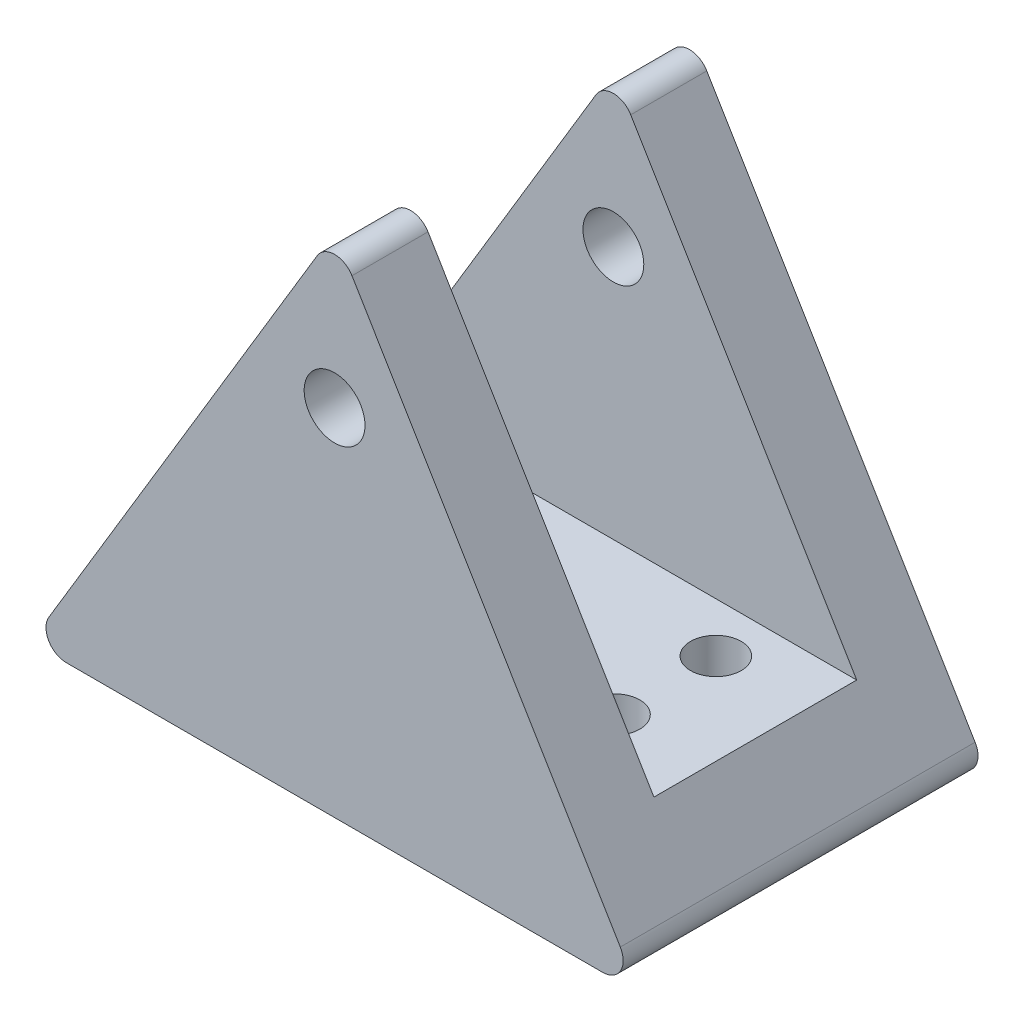
SolidWorks part; units mm, degrees
material "6061-T6 (SS)"
ref_plane "Front Plane" through (0, 0, 0) normal (0, 0, 1) x (1, 0, 0)
ref_plane "Top Plane" through (0, 0, 0) normal (0, 1, 0) x (1, 0, 0)
ref_plane "Right Plane" through (0, 0, 0) normal (1, 0, 0) x (0, 0, -1)
sketch "Sketch2" plane through (0, 0, 0) normal (0, 0, 1) x (1, 0, 0)
  line L1 (-38.1, 31.75) -> (38.1, 31.75)
  line L2 (-38.1, 31.75) -> (-38.1, -31.75)
  line L3 (-38.1, -31.75) -> (38.1, -31.75)
  line L4 (38.1, 31.75) -> (38.1, -31.75)
  line L5 (-38.1, 31.75) -> (38.1, -31.75) construction
  line L6 (-38.1, -31.75) -> (38.1, 31.75) construction
  point P0 (0, 0)
  dimension "D1" = 76.2
  dimension "D2" = 63.5
extrude "Boss-Extrude1" add sketch "Sketch2" along normal blind 44.45
sketch "Sketch3" plane through (0, 0, 44.45) normal (0, 0, 1) x (1, 0, 0)
  line L0 (0, 31.75) -> (0, -31.75) construction
  line L1 (-38.1, -31.75) -> (38.1, -31.75) construction
  line L2 (-38.1, -31.75) -> (0, 31.75)
  line L4 (-38.1, 31.75) -> (-38.1, -31.75)
  line L7 (-38.1, 31.75) -> (0, 31.75)
  point P6 (0, 0)
sketch "Sketch5" plane through (38.1, 0, 0) normal (1, 0, 0) x (0, 0, -1)
  line L0 (0, 0) -> (-44.45, 0) construction
  line L1 (-44.45, 0) -> (-22.225, 31.75) construction
  line L2 (-44.45, 31.75) -> (0, 31.75) construction
  line L3 (-22.225, 31.75) -> (-22.225, -31.75) construction
  line L4 (-44.45, -31.75) -> (0, -31.75) construction
  line L5 (-34.925, -19.05) -> (-9.525, -19.05)
  line L6 (-34.925, -19.05) -> (-34.925, 31.75)
  line L7 (-34.925, 31.75) -> (-9.525, 31.75)
  line L8 (-9.525, 31.75) -> (-9.525, -19.05)
  point P13 (-22.225, -19.05)
  dimension "D1" = 25.4
  dimension "D2" = 50.8
extrude "Cut-Extrude3" cut sketch "Sketch5" against normal through all
extrude "Cut-Extrude4" cut sketch "Sketch3" against normal blind 44.45
sketch "Sketch6" plane through (0, 0, 44.45) normal (0, 0, 1) x (1, 0, 0)
  line L0 (0, 31.75) -> (38.1, -31.75)
  line L1 (38.1, -31.75) -> (38.1, 31.75)
  line L2 (38.1, 31.75) -> (0, 31.75)
extrude "Cut-Extrude5" cut sketch "Sketch6" against normal through all
sketch "Sketch7" plane through (0, -19.05, 0) normal (0, 1, 0) x (1, 0, 0)
  line L0 (0, 0) -> (0, -44.1741) construction
  line L1 (-30.48, -22.087) -> (30.48, -22.087) construction
  line L2 (30.48, -34.925) -> (30.48, -9.525) construction
  line L4 (-38.1, -44.45) -> (-38.1, 0) construction
  circle A0 centre (-19.05, -15.737) radius 3.175
  circle A1 centre (19.05, -15.737) radius 3.175
  circle A2 centre (19.05, -28.437) radius 3.175
  circle A3 centre (-19.05, -28.437) radius 3.175
  point P9 (0, -22.087)
  dimension "D1" = 6.35
  dimension "D2" = 6.35
  dimension "D3" = 19.05
extrude "Cut-Extrude6" cut sketch "Sketch7" against normal blind 44.45
sketch "Sketch8" plane through (0, 0, 44.45) normal (0, 0, 1) x (1, 0, 0)
  line L0 (0, 31.75) -> (0, 8.89) construction
  circle A0 centre (0, 12.7) radius 3.81
  point P6 (0, 0)
  dimension "D1" = 7.62
  dimension "D2" = 19.05
extrude "Cut-Extrude7" cut sketch "Sketch8" against normal through all
fillet "Fillet3" radius 2.54 4 edges at (38.1, -31.75, 22.225) (0, 31.75, 39.6875) (0, 31.75, 4.7625) (-38.1, -31.75, 22.225)
